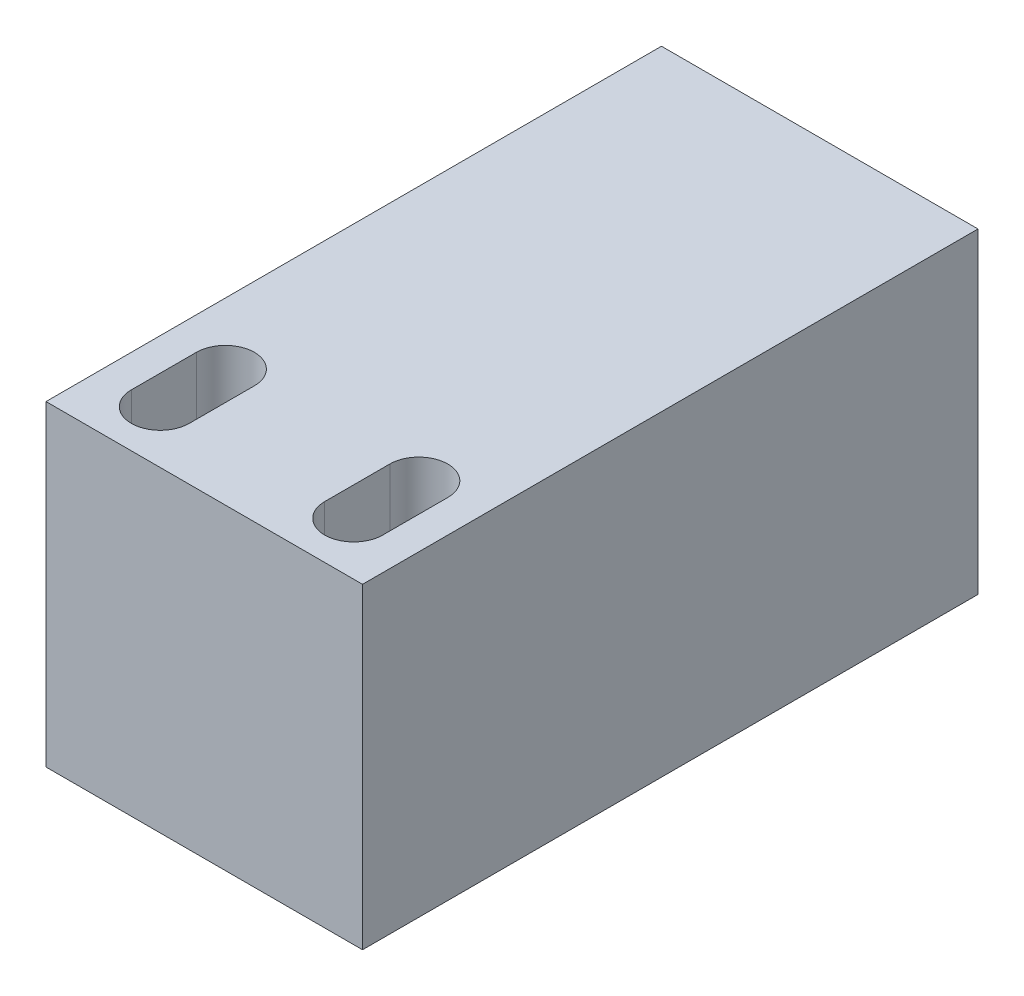
SolidWorks part; units mm, degrees
ref_plane "前视基准面" through (0, 0, 0) normal (0, 0, 1) x (1, 0, 0)
ref_plane "上视基准面" through (0, 0, 0) normal (0, 1, 0) x (1, 0, 0)
ref_plane "右视基准面" through (0, 0, 0) normal (1, 0, 0) x (0, 0, -1)
sketch "草图1" plane through (0, 0, 0) normal (0, 0, 1) x (1, 0, 0)
  line L1 (-9, 9) -> (9, 9)
  line L2 (-9, 9) -> (-9, -9)
  line L3 (-9, -9) -> (9, -9)
  line L4 (9, 9) -> (9, -9)
  line L5 (-9, 9) -> (9, -9) construction
  line L6 (-9, -9) -> (9, 9) construction
  point P0 (0, 0)
  dimension "D1" = 18
  dimension "D2" = 18
extrude "拉伸1" add sketch "草图1" along normal blind 35
sketch "草图2" plane through (0, 9, 0) normal (0, 1, 0) x (1, 0, 0)
  line L0 (5.5, -32) -> (5.5, -28.3) construction
  line L1 (3.85, -32) -> (3.85, -28.3)
  line L2 (7.15, -32) -> (7.15, -28.3)
  line L3 (-5.5, -32) -> (-5.5, -28.3) construction
  line L4 (-7.15, -32) -> (-7.15, -28.3)
  line L5 (-3.85, -32) -> (-3.85, -28.3)
  line L6 (9, -35) -> (-9, -35) construction
  line L7 (9, -35) -> (9, 0) construction
  arc A0 (3.85, -32) -> (7.15, -32) centre (5.5, -32) ccw
  arc A1 (7.15, -28.3) -> (3.85, -28.3) centre (5.5, -28.3) ccw
  arc A2 (-7.15, -32) -> (-3.85, -32) centre (-5.5, -32) ccw
  arc A3 (-3.85, -28.3) -> (-7.15, -28.3) centre (-5.5, -28.3) ccw
  point P2 (5.5, -30.15)
  point P7 (-5.5, -30.15)
  dimension "D8" = 3.5
  dimension "D1" = 3.3
  dimension "D2" = 3.7
  dimension "D3" = 3.3
  dimension "D4" = 3.7
  dimension "D5" = 3
  dimension "D6" = 3
  dimension "D7" = 11
extrude "拉伸2" cut sketch "草图2" against normal blind 35
